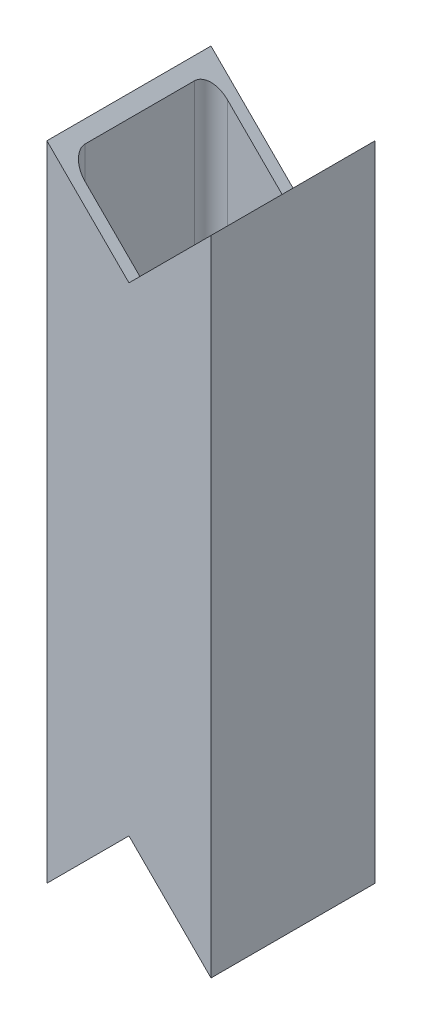
SolidWorks part; units mm, degrees
ref_plane "Plan de face" through (0, 0, 0) normal (0, 0, 1) x (1, 0, 0)
ref_plane "Plan de dessus" through (0, 0, 0) normal (0, 1, 0) x (1, 0, 0)
ref_plane "Plan de droite" through (0, 0, 0) normal (1, 0, 0) x (0, 0, -1)
sketch "Esquisse1" plane through (0, 0, 0) normal (0, 0, 1) x (1, 0, 0)
  line L0 (15, 15) -> (15, 129.9827) construction
  line L2 (0, 0) -> (0, 117.5696)
  line L4 (30, 0) -> (30, 117.5696)
  line L5 (30, 117.5696) -> (15, 102.5696)
  line L6 (15, 102.5696) -> (0, 117.5696)
  line L7 (0, 0) -> (15, 15)
  line L8 (15, 15) -> (30, 0)
  dimension "D1" = 30
extrude "Boss.-Extru.1" add sketch "Esquisse1" along normal blind 30
sketch "Esquisse2" plane through (0, 0, 0) normal (0, 1, 0) x (1, 0, 0)
  line L0 (15, -30) -> (15, 0) construction
  line L1 (5, -28) -> (25, -28)
  line L2 (2, -25) -> (2, -5)
  line L3 (5, -2) -> (25, -2)
  line L4 (28, -25) -> (28, -5)
  line L5 (15, -2) -> (15, -28) construction
  line L6 (2, -15) -> (28, -15) construction
  arc A0 (5, -28) -> (2, -25) centre (5, -25) cw
  arc A1 (25, -28) -> (28, -25) centre (25, -25) ccw
  arc A2 (25, -2) -> (28, -5) centre (25, -5) cw
  arc A3 (2, -5) -> (5, -2) centre (5, -5) cw
  point P0 (15, -15)
  point P11 (2, -28)
  point P18 (2, -2)
  dimension "D3" = 3
  dimension "D1" = 26
  dimension "D2" = 26
extrude "Enlèv. mat.-Extru.1" cut sketch "Esquisse2" along normal blind 171
